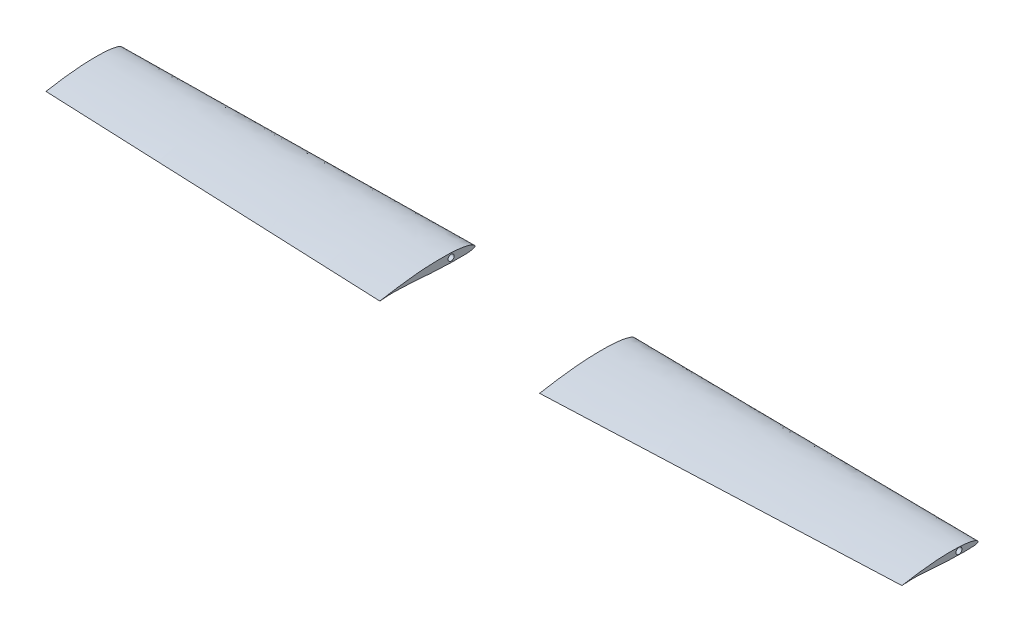
SolidWorks part; units mm, degrees
material "Foam"
ref_plane "Piano frontale" through (0, 0, 0) normal (0, 0, 1) x (1, 0, 0)
ref_plane "Piano superiore" through (0, 0, 0) normal (0, 1, 0) x (1, 0, 0)
ref_plane "Piano destro" through (0, 0, 0) normal (1, 0, 0) x (0, 0, -1)
curve "CurvaProfiloDestro250"
  spline degree 3 poles (210, 43.3424, 123.285) (210, 43.117, 125.4273) (210, 43.4162, 123.3284) (210, 43.7229, 121.6445) (210, 44.4159, 117.6221) (210, 45.2689, 112.7464) (210, 46.3518, 106.3634) (210, 47.4633, 98.9772) (210, 48.9012, 90.5604) (210, 50.3015, 81.3004) (210, 51.8024, 71.1631) (210, 53.2862, 60.3524) (210, 54.7193, 48.9891) (210, 56.0516, 37.1914) (210, 57.2293, 25.0724) (210, 58.2223, 12.7438) (210, 58.9956, 0.3116) (210, 59.5534, -12.1112) (210, 59.8967, -24.403) (210, 60.0348, -36.4331) (210, 59.962, -48.0686) (210, 59.6641, -59.1835) (210, 59.1309, -69.6671) (210, 58.3294, -79.427) (210, 57.2678, -88.3926) (210, 55.9584, -96.5028) (210, 54.4539, -103.7012) (210, 52.8113, -109.9251) (210, 51.0836, -115.1191) (210, 49.2882, -119.2301) (210, 47.4084, -122.2711) (210, 45.4757, -124.1874) (210, 43.9627, -124.9688) (210, 42.7595, -125.0213) (210, 41.4585, -124.5051) (210, 40.3042, -122.3747) (210, 39.1296, -119.3023) (210, 38.2413, -114.9281) (210, 37.5726, -109.3738) (210, 37.1578, -102.5878) (210, 36.905, -94.6381) (210, 36.7886, -85.6028) (210, 36.8146, -75.6013) (210, 36.9515, -64.7547) (210, 37.2224, -53.1982) (210, 37.6332, -41.0592) (210, 38.2314, -28.4539) (210, 39.0173, -15.4799) (210, 39.9504, -2.2329) (210, 40.9791, 11.1764) (210, 42.022, 24.6158) (210, 43.0098, 37.9314) (210, 43.876, 50.9537) (210, 44.5596, 63.4999) (210, 45.0032, 75.3712) (210, 45.1376, 86.3376) (210, 44.9932, 96.1842) (210, 44.6673, 104.6804) (210, 44.2441, 111.8065) (210, 43.8557, 117.1894) (210, 43.4787, 121.5181) (210, 43.3424, 123.285) (210, 43.117, 125.4273) (210, 43.4162, 123.3284) knots -0.014202 -0.006329 -0.001589 0 0.001576 0.006211 0.01368 0.023764 0.036307 0.051658 0.068045 0.086769 0.107053 0.128647 0.151303 0.174786 0.19886 0.223309 0.247929 0.272522 0.296848 0.320648 0.343669 0.365658 0.3864 0.405741 0.423561 0.439779 0.454311 0.467034 0.477831 0.486643 0.493542 0.498786 0.50271 0.50309 0.505896 0.510322 0.516831 0.525521 0.536535 0.549945 0.565696 0.583577 0.603379 0.624844 0.647727 0.671743 0.696673 0.722357 0.748609 0.77521 0.801891 0.828329 0.854175 0.879074 0.902636 0.924421 0.943939 0.960827 0.974827 0.985798 0.993671 0.998411 1 1.001576 1.006211 1.01368 periodic
ref_plane "PianoInternoDestro" through (210, 0, 0) normal (1, 0, 0) x (0, 0, -1)
sketch "ProfiloDestro250" plane through (210, 0, 0) normal (1, 0, 0) x (0, 0, -1)
  line L0 (-125, 43.17) -> (125.0001, 43.1874) construction
  line L1 (125.0001, 43.1874) -> (124.9987, 63.1874) construction
  line L2 (62.4987, 37.015) -> (62.4987, 59.4797) construction
  circle A0 centre (62.4987, 48.2474) radius 8 construction
  spline S0 degree 3 poles (-123.3284, 43.4162) (-125.4273, 43.117) (-123.285, 43.3424) (-121.5181, 43.4787) (-117.1894, 43.8557) (-111.8065, 44.2441) (-104.6804, 44.6673) (-96.1842, 44.9932) (-86.3376, 45.1376) (-75.3712, 45.0032) (-63.4999, 44.5596) (-50.9537, 43.876) (-37.9314, 43.0098) (-24.6158, 42.022) (-11.1764, 40.9791) (2.2329, 39.9504) (15.4799, 39.0173) (28.4539, 38.2314) (41.0592, 37.6332) (53.1982, 37.2224) (64.7547, 36.9515) (75.6013, 36.8146) (85.6028, 36.7886) (94.6381, 36.905) (102.5878, 37.1578) (109.3738, 37.5726) (114.9281, 38.2413) (119.3023, 39.1296) (122.3747, 40.3042) (124.5051, 41.4585) (125.0213, 42.7595) (124.9688, 43.9627) (124.1874, 45.4757) (122.2711, 47.4084) (119.2301, 49.2882) (115.1191, 51.0836) (109.9251, 52.8113) (103.7012, 54.4539) (96.5028, 55.9584) (88.3926, 57.2678) (79.427, 58.3294) (69.6671, 59.1309) (59.1835, 59.6641) (48.0686, 59.962) (36.4331, 60.0348) (24.403, 59.8967) (12.1112, 59.5534) (-0.3116, 58.9956) (-12.7438, 58.2223) (-25.0724, 57.2293) (-37.1914, 56.0516) (-48.9891, 54.7193) (-60.3524, 53.2862) (-71.1631, 51.8024) (-81.3004, 50.3015) (-90.5604, 48.9012) (-98.9772, 47.4633) (-106.3634, 46.3518) (-112.7464, 45.2689) (-117.6221, 44.4159) (-121.6445, 43.7229) (-123.3284, 43.4162) (-125.4273, 43.117) (-123.285, 43.3424) knots -0.01368 -0.006211 -0.001576 0 0.001589 0.006329 0.014202 0.025173 0.039173 0.056061 0.075579 0.097364 0.120926 0.145825 0.171671 0.198109 0.22479 0.251391 0.277643 0.303327 0.328257 0.352273 0.375156 0.396621 0.416423 0.434304 0.450055 0.463465 0.474479 0.483169 0.489678 0.494104 0.49691 0.49729 0.501214 0.506458 0.513357 0.522169 0.532966 0.545689 0.560221 0.576439 0.594259 0.6136 0.634342 0.656331 0.679352 0.703152 0.727478 0.752071 0.776691 0.80114 0.825214 0.848697 0.871353 0.892947 0.913231 0.931955 0.948342 0.963693 0.976236 0.98632 0.993789 0.998424 1 1.001589 1.006329 1.014202 only from (-125, 43.17) to (-125, 43.17) construction
  spline S1 degree 3 poles (-123.3284, 43.4162) (-125.4273, 43.117) (-123.285, 43.3424) (-121.5181, 43.4787) (-117.1894, 43.8557) (-111.8065, 44.2441) (-104.6804, 44.6673) (-96.1842, 44.9932) (-86.3376, 45.1376) (-75.3712, 45.0032) (-63.4999, 44.5596) (-50.9537, 43.876) (-37.9314, 43.0098) (-24.6158, 42.022) (-11.1764, 40.9791) (2.2329, 39.9504) (15.4799, 39.0173) (28.4539, 38.2314) (41.0592, 37.6332) (53.1982, 37.2224) (64.7547, 36.9515) (75.6013, 36.8146) (85.6028, 36.7886) (94.6381, 36.905) (102.5878, 37.1578) (109.3738, 37.5726) (114.9281, 38.2413) (119.3023, 39.1296) (122.3747, 40.3042) (124.5051, 41.4585) (125.0213, 42.7595) (124.9688, 43.9627) (124.1874, 45.4757) (122.2711, 47.4084) (119.2301, 49.2882) (115.1191, 51.0836) (109.9251, 52.8113) (103.7012, 54.4539) (96.5028, 55.9584) (88.3926, 57.2678) (79.427, 58.3294) (69.6671, 59.1309) (59.1835, 59.6641) (48.0686, 59.962) (36.4331, 60.0348) (24.403, 59.8967) (12.1112, 59.5534) (-0.3116, 58.9956) (-12.7438, 58.2223) (-25.0724, 57.2293) (-37.1914, 56.0516) (-48.9891, 54.7193) (-60.3524, 53.2862) (-71.1631, 51.8024) (-81.3004, 50.3015) (-90.5604, 48.9012) (-98.9772, 47.4633) (-106.3634, 46.3518) (-112.7464, 45.2689) (-117.6221, 44.4159) (-121.6445, 43.7229) (-123.3284, 43.4162) (-125.4273, 43.117) (-123.285, 43.3424) knots -0.01368 -0.006211 -0.001576 0 0.001589 0.006329 0.014202 0.025173 0.039173 0.056061 0.075579 0.097364 0.120926 0.145825 0.171671 0.198109 0.22479 0.251391 0.277643 0.303327 0.328257 0.352273 0.375156 0.396621 0.416423 0.434304 0.450055 0.463465 0.474479 0.483169 0.489678 0.494104 0.49691 0.49729 0.501214 0.506458 0.513357 0.522169 0.532966 0.545689 0.560221 0.576439 0.594259 0.6136 0.634342 0.656331 0.679352 0.703152 0.727478 0.752071 0.776691 0.80114 0.825214 0.848697 0.871353 0.892947 0.913231 0.931955 0.948342 0.963693 0.976236 0.98632 0.993789 0.998424 1 1.001589 1.006329 1.014202 only from (-125, 43.17) to (-125, 43.17)
  dimension "D3" = 16
  dimension "D1" = 20
  dimension "D2" = 62.5
ref_plane "PianoEsternoDestro" through (1125, 0, 0) normal (1, 0, 0) x (0, 0, -1)
curve "CurvaProfiloDestro200"
  spline degree 3 poles (1125, 44.3279, 86.128) (1125, 44.1476, 87.8419) (1125, 44.387, 86.1627) (1125, 44.6323, 84.8156) (1125, 45.1867, 81.5977) (1125, 45.8692, 77.6972) (1125, 46.7354, 72.5907) (1125, 47.6246, 66.6817) (1125, 48.775, 59.9483) (1125, 49.8952, 52.5404) (1125, 51.0959, 44.4305) (1125, 52.283, 35.7819) (1125, 53.4294, 26.6913) (1125, 54.4953, 17.2531) (1125, 55.4375, 7.5579) (1125, 56.2319, -2.305) (1125, 56.8505, -12.2507) (1125, 57.2967, -22.1889) (1125, 57.5714, -32.0224) (1125, 57.6818, -41.6464) (1125, 57.6236, -50.9549) (1125, 57.3853, -59.8468) (1125, 56.9587, -68.2337) (1125, 56.3175, -76.0416) (1125, 55.4683, -83.2141) (1125, 54.4207, -89.7023) (1125, 53.2171, -95.461) (1125, 51.9031, -100.4401) (1125, 50.5209, -104.5952) (1125, 49.0845, -107.8841) (1125, 47.5807, -110.3169) (1125, 46.0345, -111.8499) (1125, 44.8241, -112.4751) (1125, 43.8616, -112.5171) (1125, 42.8208, -112.1041) (1125, 41.8974, -110.3997) (1125, 40.9576, -107.9418) (1125, 40.247, -104.4425) (1125, 39.7121, -99.999) (1125, 39.3803, -94.5703) (1125, 39.178, -88.2105) (1125, 39.0849, -80.9822) (1125, 39.1057, -72.981) (1125, 39.2152, -64.3038) (1125, 39.4319, -55.0585) (1125, 39.7605, -45.3473) (1125, 40.2391, -35.2631) (1125, 40.8678, -24.884) (1125, 41.6143, -14.2863) (1125, 42.4373, -3.5589) (1125, 43.2716, 7.1926) (1125, 44.0618, 17.8451) (1125, 44.7548, 28.2629) (1125, 45.3017, 38.2999) (1125, 45.6566, 47.797) (1125, 45.7641, 56.5701) (1125, 45.6486, 64.4473) (1125, 45.3879, 71.2443) (1125, 45.0493, 76.9452) (1125, 44.7386, 81.2515) (1125, 44.437, 84.7145) (1125, 44.3279, 86.128) (1125, 44.1476, 87.8419) (1125, 44.387, 86.1627) knots -0.014202 -0.006329 -0.001589 0 0.001576 0.006211 0.01368 0.023764 0.036307 0.051658 0.068045 0.086769 0.107053 0.128647 0.151303 0.174786 0.19886 0.223309 0.247929 0.272522 0.296848 0.320648 0.343669 0.365658 0.3864 0.405741 0.423561 0.439779 0.454311 0.467034 0.477831 0.486643 0.493542 0.498786 0.50271 0.50309 0.505896 0.510322 0.516831 0.525521 0.536535 0.549945 0.565696 0.583577 0.603379 0.624844 0.647727 0.671743 0.696673 0.722357 0.748609 0.77521 0.801891 0.828329 0.854175 0.879074 0.902636 0.924421 0.943939 0.960827 0.974827 0.985798 0.993671 0.998411 1 1.001576 1.006211 1.01368 periodic
sketch "ProfiloDestro200" plane through (1125, 0, 0) normal (1, 0, 0) x (0, 0, -1)
  line L0 (-87.5, 44.19) -> (112.5, 44.19) construction
  line L1 (112.5, 44.19) -> (112.5, 63.1874) construction
  line L2 (62.5, 57.2377) -> (62.5, 39.266) construction
  circle A0 centre (62.5, 48.2519) radius 8 construction
  circle A1 centre (62.4987, 48.2474) radius 8 construction
  spline S0 degree 3 poles (-86.1627, 44.387) (-87.8419, 44.1476) (-86.128, 44.3279) (-84.7145, 44.437) (-81.2515, 44.7386) (-76.9452, 45.0493) (-71.2443, 45.3879) (-64.4473, 45.6486) (-56.5701, 45.7641) (-47.797, 45.6566) (-38.2999, 45.3017) (-28.2629, 44.7548) (-17.8451, 44.0618) (-7.1926, 43.2716) (3.5589, 42.4373) (14.2863, 41.6143) (24.884, 40.8678) (35.2631, 40.2391) (45.3473, 39.7605) (55.0585, 39.4319) (64.3038, 39.2152) (72.981, 39.1057) (80.9822, 39.0849) (88.2105, 39.178) (94.5703, 39.3803) (99.999, 39.7121) (104.4425, 40.247) (107.9418, 40.9576) (110.3997, 41.8974) (112.1041, 42.8208) (112.5171, 43.8616) (112.4751, 44.8241) (111.8499, 46.0345) (110.3169, 47.5807) (107.8841, 49.0845) (104.5952, 50.5209) (100.4401, 51.9031) (95.461, 53.2171) (89.7023, 54.4207) (83.2141, 55.4683) (76.0416, 56.3175) (68.2337, 56.9587) (59.8468, 57.3853) (50.9549, 57.6236) (41.6464, 57.6818) (32.0224, 57.5714) (22.1889, 57.2967) (12.2507, 56.8505) (2.305, 56.2319) (-7.5579, 55.4375) (-17.2531, 54.4953) (-26.6913, 53.4294) (-35.7819, 52.283) (-44.4305, 51.0959) (-52.5404, 49.8952) (-59.9483, 48.775) (-66.6817, 47.6246) (-72.5907, 46.7354) (-77.6972, 45.8692) (-81.5977, 45.1867) (-84.8156, 44.6323) (-86.1627, 44.387) (-87.8419, 44.1476) (-86.128, 44.3279) knots -0.01368 -0.006211 -0.001576 0 0.001589 0.006329 0.014202 0.025173 0.039173 0.056061 0.075579 0.097364 0.120926 0.145825 0.171671 0.198109 0.22479 0.251391 0.277643 0.303327 0.328257 0.352273 0.375156 0.396621 0.416423 0.434304 0.450055 0.463465 0.474479 0.483169 0.489678 0.494104 0.49691 0.49729 0.501214 0.506458 0.513357 0.522169 0.532966 0.545689 0.560221 0.576439 0.594259 0.6136 0.634342 0.656331 0.679352 0.703152 0.727478 0.752071 0.776691 0.80114 0.825214 0.848697 0.871353 0.892947 0.913231 0.931955 0.948342 0.963693 0.976236 0.98632 0.993789 0.998424 1 1.001589 1.006329 1.014202 only from (-87.5, 44.19) to (-87.5, 44.19) construction
  spline S1 degree 3 poles (-86.1627, 44.387) (-87.8419, 44.1476) (-86.128, 44.3279) (-84.7145, 44.437) (-81.2515, 44.7386) (-76.9452, 45.0493) (-71.2443, 45.3879) (-64.4473, 45.6486) (-56.5701, 45.7641) (-47.797, 45.6566) (-38.2999, 45.3017) (-28.2629, 44.7548) (-17.8451, 44.0618) (-7.1926, 43.2716) (3.5589, 42.4373) (14.2863, 41.6143) (24.884, 40.8678) (35.2631, 40.2391) (45.3473, 39.7605) (55.0585, 39.4319) (64.3038, 39.2152) (72.981, 39.1057) (80.9822, 39.0849) (88.2105, 39.178) (94.5703, 39.3803) (99.999, 39.7121) (104.4425, 40.247) (107.9418, 40.9576) (110.3997, 41.8974) (112.1041, 42.8208) (112.5171, 43.8616) (112.4751, 44.8241) (111.8499, 46.0345) (110.3169, 47.5807) (107.8841, 49.0845) (104.5952, 50.5209) (100.4401, 51.9031) (95.461, 53.2171) (89.7023, 54.4207) (83.2141, 55.4683) (76.0416, 56.3175) (68.2337, 56.9587) (59.8468, 57.3853) (50.9549, 57.6236) (41.6464, 57.6818) (32.0224, 57.5714) (22.1889, 57.2967) (12.2507, 56.8505) (2.305, 56.2319) (-7.5579, 55.4375) (-17.2531, 54.4953) (-26.6913, 53.4294) (-35.7819, 52.283) (-44.4305, 51.0959) (-52.5404, 49.8952) (-59.9483, 48.775) (-66.6817, 47.6246) (-72.5907, 46.7354) (-77.6972, 45.8692) (-81.5977, 45.1867) (-84.8156, 44.6323) (-86.1627, 44.387) (-87.8419, 44.1476) (-86.128, 44.3279) knots -0.01368 -0.006211 -0.001576 0 0.001589 0.006329 0.014202 0.025173 0.039173 0.056061 0.075579 0.097364 0.120926 0.145825 0.171671 0.198109 0.22479 0.251391 0.277643 0.303327 0.328257 0.352273 0.375156 0.396621 0.416423 0.434304 0.450055 0.463465 0.474479 0.483169 0.489678 0.494104 0.49691 0.49729 0.501214 0.506458 0.513357 0.522169 0.532966 0.545689 0.560221 0.576439 0.594259 0.6136 0.634342 0.656331 0.679352 0.703152 0.727478 0.752071 0.776691 0.80114 0.825214 0.848697 0.871353 0.892947 0.913231 0.931955 0.948342 0.963693 0.976236 0.98632 0.993789 0.998424 1 1.001589 1.006329 1.014202 only from (-87.5, 44.19) to (-87.5, 44.19)
  point P11 (62.5, 48.2519)
  dimension "D1" = 50
ref_plane "PianoVerticaleCentroLongherone" through (0, 0, -62.4987) normal (0, 0, 1) x (1, 0, 0)
loft "Ala" add profiles "ProfiloDestro250", "ProfiloDestro200"
sketch "Schizzo6" plane through (1125, 0, 0) normal (1, 0, 0) x (0, 0, -1)
  circle A0 centre (62.5, 48.2519) radius 8
  circle A1 centre (62.5, 48.2519) radius 8 construction
extrude "ForoLongheroneDestro" cut sketch "Schizzo6" against normal through all
ref_plane "PianoEsternoSinistro" through (-1125, 0, 0) normal (1, 0, 0) x (0, 0, -1)
ref_plane "PianoInternoSinistro" through (-210, 0, 0) normal (1, 0, 0) x (0, 0, -1)
curve "CurvaProfiloSinistro200"
  spline degree 3 poles (-1125, 44.3279, 86.128) (-1125, 44.1476, 87.8419) (-1125, 44.387, 86.1627) (-1125, 44.6323, 84.8156) (-1125, 45.1867, 81.5977) (-1125, 45.8692, 77.6972) (-1125, 46.7354, 72.5907) (-1125, 47.6246, 66.6817) (-1125, 48.775, 59.9483) (-1125, 49.8952, 52.5404) (-1125, 51.0959, 44.4305) (-1125, 52.283, 35.7819) (-1125, 53.4294, 26.6913) (-1125, 54.4953, 17.2531) (-1125, 55.4375, 7.5579) (-1125, 56.2319, -2.305) (-1125, 56.8505, -12.2507) (-1125, 57.2967, -22.1889) (-1125, 57.5714, -32.0224) (-1125, 57.6818, -41.6464) (-1125, 57.6236, -50.9549) (-1125, 57.3853, -59.8468) (-1125, 56.9587, -68.2337) (-1125, 56.3175, -76.0416) (-1125, 55.4683, -83.2141) (-1125, 54.4207, -89.7023) (-1125, 53.2171, -95.461) (-1125, 51.9031, -100.4401) (-1125, 50.5209, -104.5952) (-1125, 49.0845, -107.8841) (-1125, 47.5807, -110.3169) (-1125, 46.0345, -111.8499) (-1125, 44.8241, -112.4751) (-1125, 43.8616, -112.5171) (-1125, 42.8208, -112.1041) (-1125, 41.8974, -110.3997) (-1125, 40.9576, -107.9418) (-1125, 40.247, -104.4425) (-1125, 39.7121, -99.999) (-1125, 39.3803, -94.5703) (-1125, 39.178, -88.2105) (-1125, 39.0849, -80.9822) (-1125, 39.1057, -72.981) (-1125, 39.2152, -64.3038) (-1125, 39.4319, -55.0585) (-1125, 39.7605, -45.3473) (-1125, 40.2391, -35.2631) (-1125, 40.8678, -24.884) (-1125, 41.6143, -14.2863) (-1125, 42.4373, -3.5589) (-1125, 43.2716, 7.1926) (-1125, 44.0618, 17.8451) (-1125, 44.7548, 28.2629) (-1125, 45.3017, 38.2999) (-1125, 45.6566, 47.797) (-1125, 45.7641, 56.5701) (-1125, 45.6486, 64.4473) (-1125, 45.3879, 71.2443) (-1125, 45.0493, 76.9452) (-1125, 44.7386, 81.2515) (-1125, 44.437, 84.7145) (-1125, 44.3279, 86.128) (-1125, 44.1476, 87.8419) (-1125, 44.387, 86.1627) knots -0.014202 -0.006329 -0.001589 0 0.001576 0.006211 0.01368 0.023764 0.036307 0.051658 0.068045 0.086769 0.107053 0.128647 0.151303 0.174786 0.19886 0.223309 0.247929 0.272522 0.296848 0.320648 0.343669 0.365658 0.3864 0.405741 0.423561 0.439779 0.454311 0.467034 0.477831 0.486643 0.493542 0.498786 0.50271 0.50309 0.505896 0.510322 0.516831 0.525521 0.536535 0.549945 0.565696 0.583577 0.603379 0.624844 0.647727 0.671743 0.696673 0.722357 0.748609 0.77521 0.801891 0.828329 0.854175 0.879074 0.902636 0.924421 0.943939 0.960827 0.974827 0.985798 0.993671 0.998411 1 1.001576 1.006211 1.01368 periodic
curve "CurvaprofiloSinistro250"
  spline degree 3 poles (-210, 43.3424, 123.285) (-210, 43.117, 125.4273) (-210, 43.4162, 123.3284) (-210, 43.7229, 121.6445) (-210, 44.4159, 117.6221) (-210, 45.2689, 112.7464) (-210, 46.3518, 106.3634) (-210, 47.4633, 98.9772) (-210, 48.9012, 90.5604) (-210, 50.3015, 81.3004) (-210, 51.8024, 71.1631) (-210, 53.2862, 60.3524) (-210, 54.7193, 48.9891) (-210, 56.0516, 37.1914) (-210, 57.2293, 25.0724) (-210, 58.2223, 12.7438) (-210, 58.9956, 0.3116) (-210, 59.5534, -12.1112) (-210, 59.8967, -24.403) (-210, 60.0348, -36.4331) (-210, 59.962, -48.0686) (-210, 59.6641, -59.1835) (-210, 59.1309, -69.6671) (-210, 58.3294, -79.427) (-210, 57.2678, -88.3926) (-210, 55.9584, -96.5028) (-210, 54.4539, -103.7012) (-210, 52.8113, -109.9251) (-210, 51.0836, -115.1191) (-210, 49.2882, -119.2301) (-210, 47.4084, -122.2711) (-210, 45.4757, -124.1874) (-210, 43.9627, -124.9688) (-210, 42.7595, -125.0213) (-210, 41.4585, -124.5051) (-210, 40.3042, -122.3747) (-210, 39.1296, -119.3023) (-210, 38.2413, -114.9281) (-210, 37.5726, -109.3738) (-210, 37.1578, -102.5878) (-210, 36.905, -94.6381) (-210, 36.7886, -85.6028) (-210, 36.8146, -75.6013) (-210, 36.9515, -64.7547) (-210, 37.2224, -53.1982) (-210, 37.6332, -41.0592) (-210, 38.2314, -28.4539) (-210, 39.0173, -15.4799) (-210, 39.9504, -2.2329) (-210, 40.9791, 11.1764) (-210, 42.022, 24.6158) (-210, 43.0098, 37.9314) (-210, 43.876, 50.9537) (-210, 44.5596, 63.4999) (-210, 45.0032, 75.3712) (-210, 45.1376, 86.3376) (-210, 44.9932, 96.1842) (-210, 44.6673, 104.6804) (-210, 44.2441, 111.8065) (-210, 43.8557, 117.1894) (-210, 43.4787, 121.5181) (-210, 43.3424, 123.285) (-210, 43.117, 125.4273) (-210, 43.4162, 123.3284) knots -0.014202 -0.006329 -0.001589 0 0.001576 0.006211 0.01368 0.023764 0.036307 0.051658 0.068045 0.086769 0.107053 0.128647 0.151303 0.174786 0.19886 0.223309 0.247929 0.272522 0.296848 0.320648 0.343669 0.365658 0.3864 0.405741 0.423561 0.439779 0.454311 0.467034 0.477831 0.486643 0.493542 0.498786 0.50271 0.50309 0.505896 0.510322 0.516831 0.525521 0.536535 0.549945 0.565696 0.583577 0.603379 0.624844 0.647727 0.671743 0.696673 0.722357 0.748609 0.77521 0.801891 0.828329 0.854175 0.879074 0.902636 0.924421 0.943939 0.960827 0.974827 0.985798 0.993671 0.998411 1 1.001576 1.006211 1.01368 periodic
sketch "ProfiloSinistro200" plane through (-1125, 0, 0) normal (1, 0, 0) x (0, 0, -1)
  spline S0 degree 3 poles (-86.1627, 44.387) (-87.8419, 44.1476) (-86.128, 44.3279) (-84.7145, 44.437) (-81.2515, 44.7386) (-76.9452, 45.0493) (-71.2443, 45.3879) (-64.4473, 45.6486) (-56.5701, 45.7641) (-47.797, 45.6566) (-38.2999, 45.3017) (-28.2629, 44.7548) (-17.8451, 44.0618) (-7.1926, 43.2716) (3.5589, 42.4373) (14.2863, 41.6143) (24.884, 40.8678) (35.2631, 40.2391) (45.3473, 39.7605) (55.0585, 39.4319) (64.3038, 39.2152) (72.981, 39.1057) (80.9822, 39.0849) (88.2105, 39.178) (94.5703, 39.3803) (99.999, 39.7121) (104.4425, 40.247) (107.9418, 40.9576) (110.3997, 41.8974) (112.1041, 42.8208) (112.5171, 43.8616) (112.4751, 44.8241) (111.8499, 46.0345) (110.3169, 47.5807) (107.8841, 49.0845) (104.5952, 50.5209) (100.4401, 51.9031) (95.461, 53.2171) (89.7023, 54.4207) (83.2141, 55.4683) (76.0416, 56.3175) (68.2337, 56.9587) (59.8468, 57.3853) (50.9549, 57.6236) (41.6464, 57.6818) (32.0224, 57.5714) (22.1889, 57.2967) (12.2507, 56.8505) (2.305, 56.2319) (-7.5579, 55.4375) (-17.2531, 54.4953) (-26.6913, 53.4294) (-35.7819, 52.283) (-44.4305, 51.0959) (-52.5404, 49.8952) (-59.9483, 48.775) (-66.6817, 47.6246) (-72.5907, 46.7354) (-77.6972, 45.8692) (-81.5977, 45.1867) (-84.8156, 44.6323) (-86.1627, 44.387) (-87.8419, 44.1476) (-86.128, 44.3279) knots -0.01368 -0.006211 -0.001576 0 0.001589 0.006329 0.014202 0.025173 0.039173 0.056061 0.075579 0.097364 0.120926 0.145825 0.171671 0.198109 0.22479 0.251391 0.277643 0.303327 0.328257 0.352273 0.375156 0.396621 0.416423 0.434304 0.450055 0.463465 0.474479 0.483169 0.489678 0.494104 0.49691 0.49729 0.501214 0.506458 0.513357 0.522169 0.532966 0.545689 0.560221 0.576439 0.594259 0.6136 0.634342 0.656331 0.679352 0.703152 0.727478 0.752071 0.776691 0.80114 0.825214 0.848697 0.871353 0.892947 0.913231 0.931955 0.948342 0.963693 0.976236 0.98632 0.993789 0.998424 1 1.001589 1.006329 1.014202 only from (-87.5, 44.19) to (-87.5, 44.19) construction
  spline S1 degree 3 poles (-86.1627, 44.387) (-87.8419, 44.1476) (-86.128, 44.3279) (-84.7145, 44.437) (-81.2515, 44.7386) (-76.9452, 45.0493) (-71.2443, 45.3879) (-64.4473, 45.6486) (-56.5701, 45.7641) (-47.797, 45.6566) (-38.2999, 45.3017) (-28.2629, 44.7548) (-17.8451, 44.0618) (-7.1926, 43.2716) (3.5589, 42.4373) (14.2863, 41.6143) (24.884, 40.8678) (35.2631, 40.2391) (45.3473, 39.7605) (55.0585, 39.4319) (64.3038, 39.2152) (72.981, 39.1057) (80.9822, 39.0849) (88.2105, 39.178) (94.5703, 39.3803) (99.999, 39.7121) (104.4425, 40.247) (107.9418, 40.9576) (110.3997, 41.8974) (112.1041, 42.8208) (112.5171, 43.8616) (112.4751, 44.8241) (111.8499, 46.0345) (110.3169, 47.5807) (107.8841, 49.0845) (104.5952, 50.5209) (100.4401, 51.9031) (95.461, 53.2171) (89.7023, 54.4207) (83.2141, 55.4683) (76.0416, 56.3175) (68.2337, 56.9587) (59.8468, 57.3853) (50.9549, 57.6236) (41.6464, 57.6818) (32.0224, 57.5714) (22.1889, 57.2967) (12.2507, 56.8505) (2.305, 56.2319) (-7.5579, 55.4375) (-17.2531, 54.4953) (-26.6913, 53.4294) (-35.7819, 52.283) (-44.4305, 51.0959) (-52.5404, 49.8952) (-59.9483, 48.775) (-66.6817, 47.6246) (-72.5907, 46.7354) (-77.6972, 45.8692) (-81.5977, 45.1867) (-84.8156, 44.6323) (-86.1627, 44.387) (-87.8419, 44.1476) (-86.128, 44.3279) knots -0.01368 -0.006211 -0.001576 0 0.001589 0.006329 0.014202 0.025173 0.039173 0.056061 0.075579 0.097364 0.120926 0.145825 0.171671 0.198109 0.22479 0.251391 0.277643 0.303327 0.328257 0.352273 0.375156 0.396621 0.416423 0.434304 0.450055 0.463465 0.474479 0.483169 0.489678 0.494104 0.49691 0.49729 0.501214 0.506458 0.513357 0.522169 0.532966 0.545689 0.560221 0.576439 0.594259 0.6136 0.634342 0.656331 0.679352 0.703152 0.727478 0.752071 0.776691 0.80114 0.825214 0.848697 0.871353 0.892947 0.913231 0.931955 0.948342 0.963693 0.976236 0.98632 0.993789 0.998424 1 1.001589 1.006329 1.014202 only from (-87.5, 44.19) to (-87.5, 44.19)
sketch "ProfiloSinistro250" plane through (-210, 0, 0) normal (1, 0, 0) x (0, 0, -1)
  spline S0 degree 3 poles (-123.3284, 43.4162) (-125.4273, 43.117) (-123.285, 43.3424) (-121.5181, 43.4787) (-117.1894, 43.8557) (-111.8065, 44.2441) (-104.6804, 44.6673) (-96.1842, 44.9932) (-86.3376, 45.1376) (-75.3712, 45.0032) (-63.4999, 44.5596) (-50.9537, 43.876) (-37.9314, 43.0098) (-24.6158, 42.022) (-11.1764, 40.9791) (2.2329, 39.9504) (15.4799, 39.0173) (28.4539, 38.2314) (41.0592, 37.6332) (53.1982, 37.2224) (64.7547, 36.9515) (75.6013, 36.8146) (85.6028, 36.7886) (94.6381, 36.905) (102.5878, 37.1578) (109.3738, 37.5726) (114.9281, 38.2413) (119.3023, 39.1296) (122.3747, 40.3042) (124.5051, 41.4585) (125.0213, 42.7595) (124.9688, 43.9627) (124.1874, 45.4757) (122.2711, 47.4084) (119.2301, 49.2882) (115.1191, 51.0836) (109.9251, 52.8113) (103.7012, 54.4539) (96.5028, 55.9584) (88.3926, 57.2678) (79.427, 58.3294) (69.6671, 59.1309) (59.1835, 59.6641) (48.0686, 59.962) (36.4331, 60.0348) (24.403, 59.8967) (12.1112, 59.5534) (-0.3116, 58.9956) (-12.7438, 58.2223) (-25.0724, 57.2293) (-37.1914, 56.0516) (-48.9891, 54.7193) (-60.3524, 53.2862) (-71.1631, 51.8024) (-81.3004, 50.3015) (-90.5604, 48.9012) (-98.9772, 47.4633) (-106.3634, 46.3518) (-112.7464, 45.2689) (-117.6221, 44.4159) (-121.6445, 43.7229) (-123.3284, 43.4162) (-125.4273, 43.117) (-123.285, 43.3424) knots -0.01368 -0.006211 -0.001576 0 0.001589 0.006329 0.014202 0.025173 0.039173 0.056061 0.075579 0.097364 0.120926 0.145825 0.171671 0.198109 0.22479 0.251391 0.277643 0.303327 0.328257 0.352273 0.375156 0.396621 0.416423 0.434304 0.450055 0.463465 0.474479 0.483169 0.489678 0.494104 0.49691 0.49729 0.501214 0.506458 0.513357 0.522169 0.532966 0.545689 0.560221 0.576439 0.594259 0.6136 0.634342 0.656331 0.679352 0.703152 0.727478 0.752071 0.776691 0.80114 0.825214 0.848697 0.871353 0.892947 0.913231 0.931955 0.948342 0.963693 0.976236 0.98632 0.993789 0.998424 1 1.001589 1.006329 1.014202 only from (-125, 43.17) to (-125, 43.17) construction
  spline S1 degree 3 poles (-123.3284, 43.4162) (-125.4273, 43.117) (-123.285, 43.3424) (-121.5181, 43.4787) (-117.1894, 43.8557) (-111.8065, 44.2441) (-104.6804, 44.6673) (-96.1842, 44.9932) (-86.3376, 45.1376) (-75.3712, 45.0032) (-63.4999, 44.5596) (-50.9537, 43.876) (-37.9314, 43.0098) (-24.6158, 42.022) (-11.1764, 40.9791) (2.2329, 39.9504) (15.4799, 39.0173) (28.4539, 38.2314) (41.0592, 37.6332) (53.1982, 37.2224) (64.7547, 36.9515) (75.6013, 36.8146) (85.6028, 36.7886) (94.6381, 36.905) (102.5878, 37.1578) (109.3738, 37.5726) (114.9281, 38.2413) (119.3023, 39.1296) (122.3747, 40.3042) (124.5051, 41.4585) (125.0213, 42.7595) (124.9688, 43.9627) (124.1874, 45.4757) (122.2711, 47.4084) (119.2301, 49.2882) (115.1191, 51.0836) (109.9251, 52.8113) (103.7012, 54.4539) (96.5028, 55.9584) (88.3926, 57.2678) (79.427, 58.3294) (69.6671, 59.1309) (59.1835, 59.6641) (48.0686, 59.962) (36.4331, 60.0348) (24.403, 59.8967) (12.1112, 59.5534) (-0.3116, 58.9956) (-12.7438, 58.2223) (-25.0724, 57.2293) (-37.1914, 56.0516) (-48.9891, 54.7193) (-60.3524, 53.2862) (-71.1631, 51.8024) (-81.3004, 50.3015) (-90.5604, 48.9012) (-98.9772, 47.4633) (-106.3634, 46.3518) (-112.7464, 45.2689) (-117.6221, 44.4159) (-121.6445, 43.7229) (-123.3284, 43.4162) (-125.4273, 43.117) (-123.285, 43.3424) knots -0.01368 -0.006211 -0.001576 0 0.001589 0.006329 0.014202 0.025173 0.039173 0.056061 0.075579 0.097364 0.120926 0.145825 0.171671 0.198109 0.22479 0.251391 0.277643 0.303327 0.328257 0.352273 0.375156 0.396621 0.416423 0.434304 0.450055 0.463465 0.474479 0.483169 0.489678 0.494104 0.49691 0.49729 0.501214 0.506458 0.513357 0.522169 0.532966 0.545689 0.560221 0.576439 0.594259 0.6136 0.634342 0.656331 0.679352 0.703152 0.727478 0.752071 0.776691 0.80114 0.825214 0.848697 0.871353 0.892947 0.913231 0.931955 0.948342 0.963693 0.976236 0.98632 0.993789 0.998424 1 1.001589 1.006329 1.014202 only from (-125, 43.17) to (-125, 43.17)
loft "Loft1" add profiles "ProfiloSinistro200", "ProfiloSinistro250"
sketch "Schizzo9" plane through (-1125, 0, 0) normal (1, 0, 0) x (0, 0, -1)
  circle A0 centre (62.5, 48.2519) radius 8
  circle A1 centre (62.5, 48.2519) radius 8 construction
extrude "ForoLongheroneSinistro" cut sketch "Schizzo9" along normal up to surface (915 mm away) up to face at (-210, 43.17, 125)
